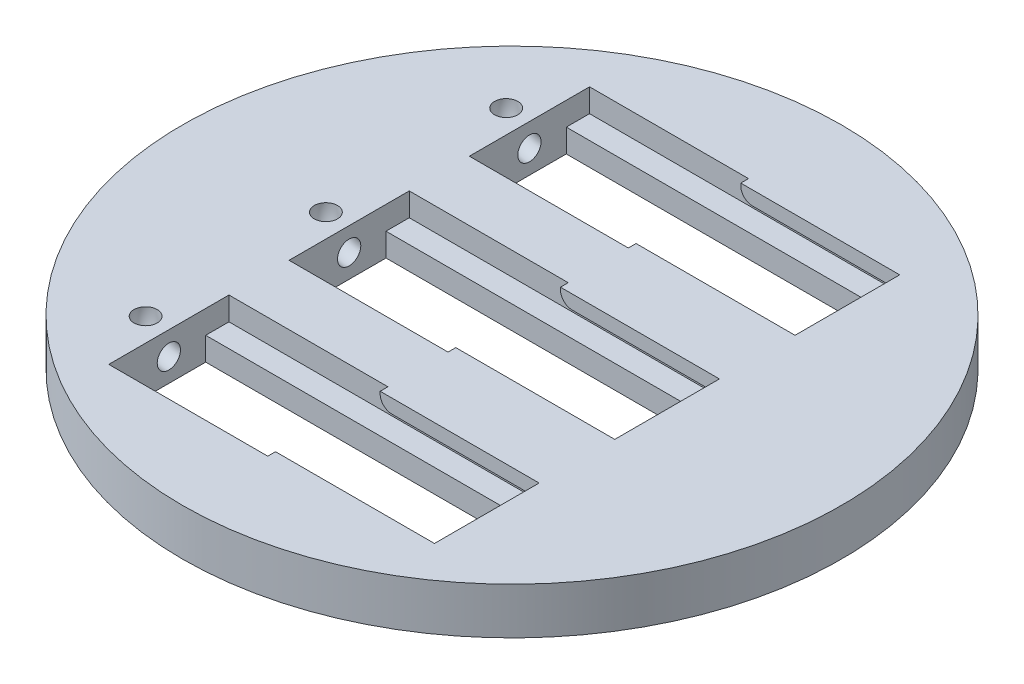
SolidWorks part; units mm, degrees
ref_plane "Front Plane" through (0, 0, 0) normal (0, 0, 1) x (1, 0, 0)
ref_plane "Top Plane" through (0, 0, 0) normal (0, 1, 0) x (1, 0, 0)
ref_plane "Right Plane" through (0, 0, 0) normal (1, 0, 0) x (0, 0, -1)
sketch "Sketch1" plane through (0, 0, 0) normal (0, 1, 0) x (1, 0, 0)
  circle A0 centre (-26.1118, -7.4004) radius 42.5
  dimension "D1" = 85
extrude "Boss-Extrude1" add sketch "Sketch1" along normal blind 6
sketch "Sketch2" plane through (0, 6, 0) normal (0, 1, 0) x (1, 0, 0)
  line L0 (-68.6118, -7.4004) -> (16.3882, -7.4004) construction
  line L1 (-26.1118, 35.0996) -> (-26.1118, -49.9004) construction
  line L2 (-26.1118, 23.0996) -> (-46.6118, 23.0996)
  line L3 (-26.1118, 23.0996) -> (-26.1118, 7.5996)
  line L4 (-26.1118, 7.5996) -> (-46.6118, 7.5996)
  line L5 (-46.6118, 23.0996) -> (-46.6118, 7.5996)
  circle A0 centre (-26.1118, -7.4004) radius 42.5 construction
  point P3 (-26.1118, -7.4004)
  point P12 (-26.1118, -7.4004)
  dimension "D1" = 15.5
  dimension "D2" = 20.5
  dimension "D3" = 15
extrude "Cut-Extrude1" cut sketch "Sketch2" against normal blind 3
sketch "Sketch3" plane through (-26.1118, 0, 0) normal (-1, 0, 0) x (0, 0, 1)
  line L0 (-15.3496, 6) -> (-15.3496, 3) construction
  line L1 (-7.5996, 6) -> (-23.0996, 6) construction
  line L2 (-7.5996, 3) -> (-23.0996, 3) construction
  line L3 (-7.5996, 3) -> (-7.5996, 6) construction
  line L4 (-23.0996, 3) -> (-7.5996, 3)
  line L5 (-23.0996, 3) -> (-23.0996, 4.2)
  line L6 (-23.0996, 4.2) -> (-22.0996, 4.2)
  line L7 (-7.5996, 3) -> (-7.5996, 4.2)
  line L8 (-8.5996, 4.2) -> (-7.5996, 4.2)
  line L10 (-22.0996, 4.2) -> (-22.0996, 6)
  line L11 (-22.0996, 6) -> (-8.5996, 6)
  line L12 (-8.5996, 4.2) -> (-8.5996, 6)
  line L13 (-23.0996, 3) -> (-23.0996, 6) construction
  point P17 (-15.3496, 6)
  dimension "D1" = 1.2
  dimension "D2" = 1
extrude "Cut-Extrude2" cut sketch "Sketch3" against normal blind 20.5
sketch "Sketch4" plane through (0, 3, 0) normal (0, 1, 0) x (1, 0, 0)
  line L0 (-5.6118, 23.0996) -> (-5.6118, 7.5996) construction
  line L1 (-5.6118, 20.0996) -> (-46.6118, 20.0996)
  line L2 (-5.6118, 20.0996) -> (-5.6118, 10.5996)
  line L3 (-5.6118, 10.5996) -> (-46.6118, 10.5996)
  line L4 (-46.6118, 20.0996) -> (-46.6118, 10.5996)
  line L5 (-46.6118, 23.0996) -> (-46.6118, 7.5996) construction
  line L6 (-5.6118, 23.0996) -> (-46.6118, 23.0996) construction
  point P8 (-46.6118, 15.3496)
  point P9 (-46.6118, 15.3496)
  dimension "D1" = 3
extrude "Cut-Extrude3" cut sketch "Sketch4" against normal up to next
sketch "Sketch5" plane through (-46.6118, 0, 0) normal (1, 0, 0) x (0, 0, -1)
  line L0 (23.0996, 6) -> (7.5996, 6) construction
  circle A0 centre (15.3485, 3) radius 1.5
  dimension "D1" = 3
  dimension "D2" = 3
revolve "Cut-Revolve1" cut sketch "Sketch5" angle 360 about axis through (-46.6118, 6, -23.0996) along (0, 0, 1)
fillet "Fillet1" radius 1.5 2 edges at (-26.1118, 4.2, -8.0996) (-26.1118, 4.2, -22.5996)
pattern_linear "LPattern4" count 3 spacing 23.25 along (0, 0, 1) of "Cut-Extrude1", "Cut-Revolve1", "Cut-Extrude3", "Cut-Extrude2", "Fillet1"
